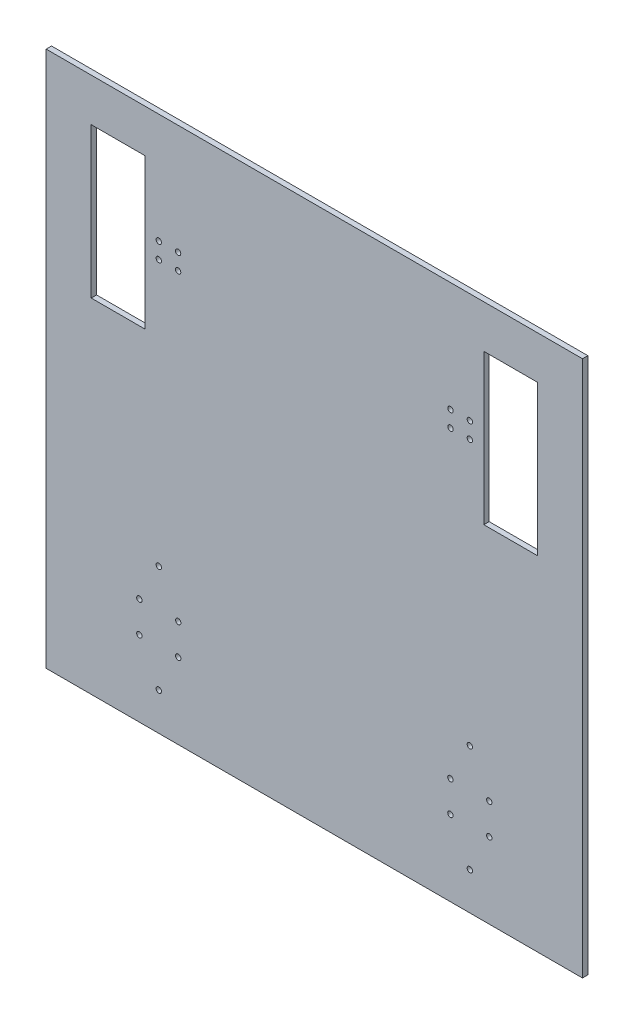
SolidWorks part; units mm, degrees
ref_plane "Front Plane" through (0, 0, 0) normal (0, 0, 1) x (1, 0, 0)
ref_plane "Top Plane" through (0, 0, 0) normal (0, 1, 0) x (1, 0, 0)
ref_plane "Right Plane" through (0, 0, 0) normal (1, 0, 0) x (0, 0, -1)
sketch "Sketch1" plane through (0, 0, 0) normal (0, 0, 1) x (1, 0, 0)
  line L0 (0, 0) -> (0, 250) construction
  line L4 (-145, 147.5) -> (-145, 132.5) construction
  line L5 (-127, 132.5) -> (-145, 132.5) construction
  line L6 (-127, 147.5) -> (-127, 132.5) construction
  line L7 (-127, 147.5) -> (-145, 147.5) construction
  line L8 (250, -250) -> (250, 250)
  line L9 (-250, -250) -> (250, -250)
  line L10 (-250, 250) -> (-250, -250)
  line L11 (250, 250) -> (-250, 250)
  line L17 (127, 147.5) -> (145, 147.5) construction
  line L18 (127, 147.5) -> (127, 132.5) construction
  line L19 (127, 132.5) -> (145, 132.5) construction
  line L20 (145, 147.5) -> (145, 132.5) construction
  line L21 (208, 210) -> (158, 210)
  line L22 (208, 210) -> (208, 70)
  line L23 (208, 70) -> (158, 70)
  line L24 (158, 210) -> (158, 70)
  line L25 (-158, 210) -> (-158, 70)
  line L26 (-208, 70) -> (-158, 70)
  line L27 (-208, 210) -> (-208, 70)
  line L28 (-208, 210) -> (-158, 210)
  line L29 (-145, 147.5) -> (-145, 132.5) construction
  line L30 (-155, 147.5) -> (-155, 132.5) construction
  line L31 (135, 147.5) -> (135, 132.5) construction
  line L32 (-135, 147.5) -> (-135, 132.5) construction
  line L33 (155, 147.5) -> (155, 132.5) construction
  circle A0 centre (127, 147.5) radius 2.5
  circle A1 centre (127, 132.5) radius 2.5
  circle A4 centre (145, 132.5) radius 2.5
  circle A5 centre (145, 147.5) radius 2.5
  circle A6 centre (-145, 147.5) radius 2.5
  circle A7 centre (-145, 132.5) radius 2.5
  circle A8 centre (-127, 132.5) radius 2.5
  circle A9 centre (-127, 147.5) radius 2.5
  point P3 (0, 250)
  point P4 (-250, 0)
  point P30 (127, 140)
  point P32 (158, 140)
  dimension "D8" = 5
  dimension "D11" = 18
  dimension "D3" = 500
  dimension "D4" = 10
  dimension "D5" = 10
  dimension "D7" = 15
  dimension "D9" = 81
  dimension "D10" = 270
  dimension "D12" = 50
  dimension "D13" = 140
  dimension "D16" = 40
  dimension "D2" = 500
extrude "Boss-Extrude1" add sketch "Sketch1" along normal blind 5
sketch "Sketch2" plane through (0, 0, 5) normal (0, 0, 1) x (1, 0, 0)
  line L0 (-145, 132.5) -> (-145, -250) construction
  line L1 (-250, -250) -> (250, -250) construction
  line L2 (0, 0) -> (0, -250) construction
  line L3 (-163.125, -179.4) -> (-126.875, -179.4) construction
  line L4 (-163.125, -179.4) -> (-163.125, -150.6) construction
  line L5 (-163.125, -150.6) -> (-126.875, -150.6) construction
  line L6 (-126.875, -179.4) -> (-126.875, -150.6) construction
  line L7 (-163.125, -179.4) -> (-126.875, -150.6) construction
  line L8 (-163.125, -150.6) -> (-126.875, -179.4) construction
  line L9 (163.125, -150.6) -> (126.875, -179.4) construction
  line L10 (163.125, -179.4) -> (126.875, -150.6) construction
  line L11 (126.875, -179.4) -> (126.875, -150.6) construction
  line L12 (163.125, -150.6) -> (126.875, -150.6) construction
  line L13 (163.125, -179.4) -> (163.125, -150.6) construction
  line L14 (163.125, -179.4) -> (126.875, -179.4) construction
  circle A0 centre (-145, 132.5) radius 2.5 construction
  circle A1 centre (-145, 132.5) radius 2.5
  circle A2 centre (-145, -165) radius 35 construction
  circle A3 centre (-163.125, -150.6) radius 2.5
  circle A4 centre (-126.875, -150.6) radius 2.5
  circle A5 centre (-126.875, -179.4) radius 2.5
  circle A6 centre (-163.125, -179.4) radius 2.5
  circle A7 centre (-145, -115) radius 2.5
  circle A8 centre (-145, -215) radius 2.5
  circle A9 centre (145, -165) radius 35 construction
  circle A10 centre (145, -215) radius 2.5
  circle A11 centre (145, -115) radius 2.5
  circle A12 centre (163.125, -179.4) radius 2.5
  circle A13 centre (126.875, -179.4) radius 2.5
  circle A14 centre (126.875, -150.6) radius 2.5
  circle A15 centre (163.125, -150.6) radius 2.5
  point P23 (0, 0)
  dimension "D1" = 70
  dimension "D5" = 5
  dimension "D6" = 50
  dimension "D2" = 50
  dimension "D3" = 28.8
  dimension "D4" = 36.25
  dimension "D7" = 50
extrude "Cut-Extrude1" cut sketch "Sketch2" against normal up to next (5 mm away)
